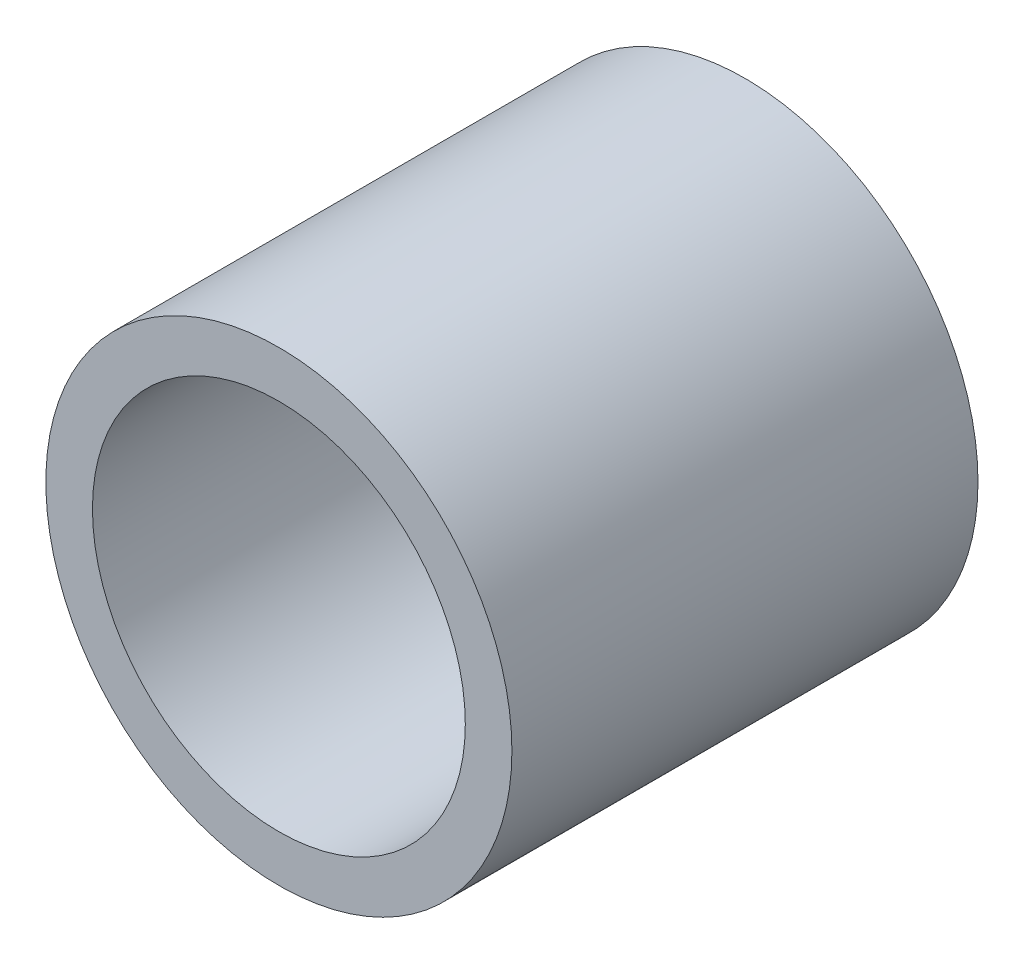
SolidWorks part; units mm, degrees
ref_plane "前视基准面" through (0, 0, 0) normal (0, 0, 1) x (1, 0, 0)
ref_plane "上视基准面" through (0, 0, 0) normal (0, 1, 0) x (1, 0, 0)
ref_plane "右视基准面" through (0, 0, 0) normal (1, 0, 0) x (0, 0, -1)
other "Configuration Table"
sketch "Profile_1" plane through (0, 0, 0) normal (0, 0, 1) x (1, 0, 0)
  circle A0 centre (0, 0) radius 5
  circle A1 centre (0, 0) radius 4
extrude "Sleeve" add sketch "Profile_1" along normal blind 10 from offset 8
